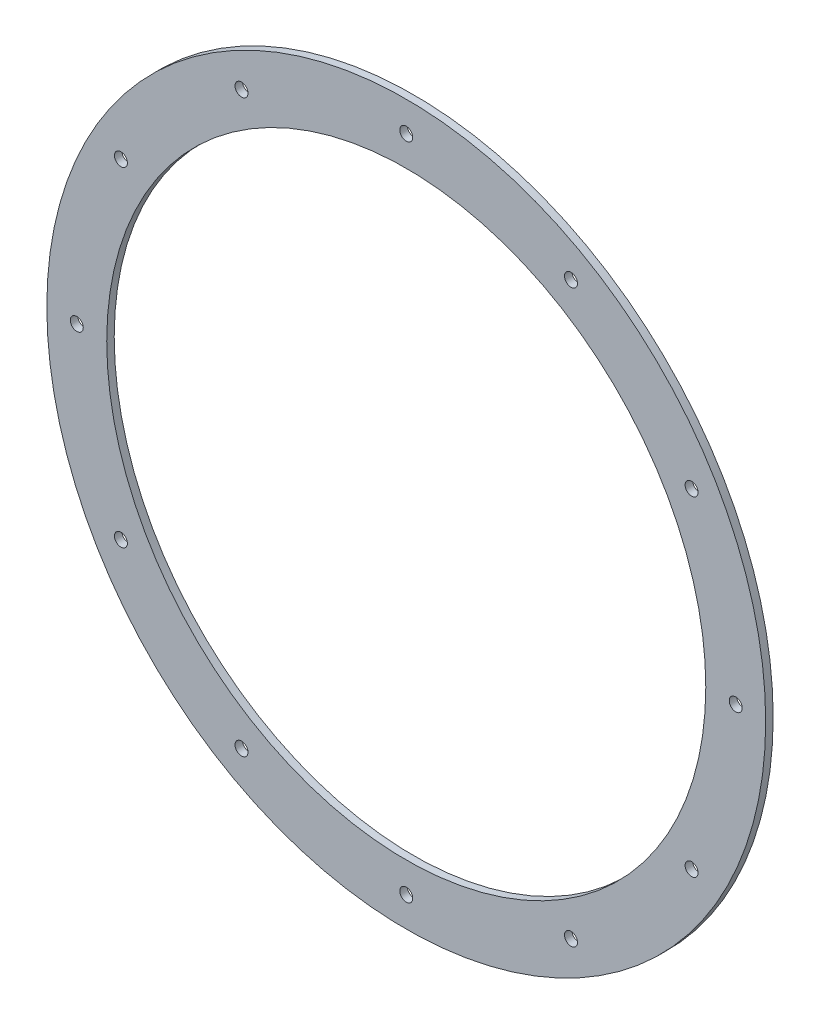
SolidWorks part; units mm, degrees
ref_plane "Front Plane" through (0, 0, 0) normal (0, 0, 1) x (1, 0, 0)
ref_plane "Top Plane" through (0, 0, 0) normal (0, 1, 0) x (1, 0, 0)
ref_plane "Right Plane" through (0, 0, 0) normal (1, 0, 0) x (0, 0, -1)
sketch "Sketch1" plane through (0, 0, 0) normal (0, 0, 1) x (1, 0, 0)
  circle A0 centre (0, 0) radius 609.6
  circle A1 centre (0, 0) radius 508
  dimension "D1" = 1219.2
  dimension "D2" = 101.6
sketch "Sketch2" plane through (0, 0, 0) normal (0, 0, 1) x (1, 0, 0)
  line L0 (0, 508) -> (0, -508) construction
  line L1 (0, -508) -> (0, -609.6) construction
  line L2 (0, 508) -> (0, 609.6) construction
  circle A0 centre (0, 215.685) radius 11
  circle A1 centre (0, 0) radius 508 construction
  circle A2 centre (0, 0) radius 609.6 construction
  circle A3 centre (0, 558.8) radius 11
  circle A4 centre (279.4, 483.935) radius 11
  circle A5 centre (483.935, 279.4) radius 11
  circle A6 centre (558.8, 0) radius 11
  circle A7 centre (483.935, -279.4) radius 11
  circle A8 centre (279.4, -483.935) radius 11
  circle A9 centre (0, -558.8) radius 11
  circle A10 centre (-279.4, -483.935) radius 11
  circle A11 centre (-483.935, -279.4) radius 11
  circle A12 centre (-558.8, 0) radius 11
  circle A13 centre (-483.935, 279.4) radius 11
  circle A14 centre (-279.4, 483.935) radius 11
  point P8 (0, 558.8)
  point P39 (0, 0)
  dimension "D1" = 22
  dimension "D2" = 22
  dimension "D3" = 12
extrude "Boss-Extrude1" add sketch "Sketch1" along normal blind 12.7
extrude "Cut-Extrude1" cut sketch "Sketch2" along direction (0, 0, 1) on the side of the normal up to surface (12.7 mm away)
